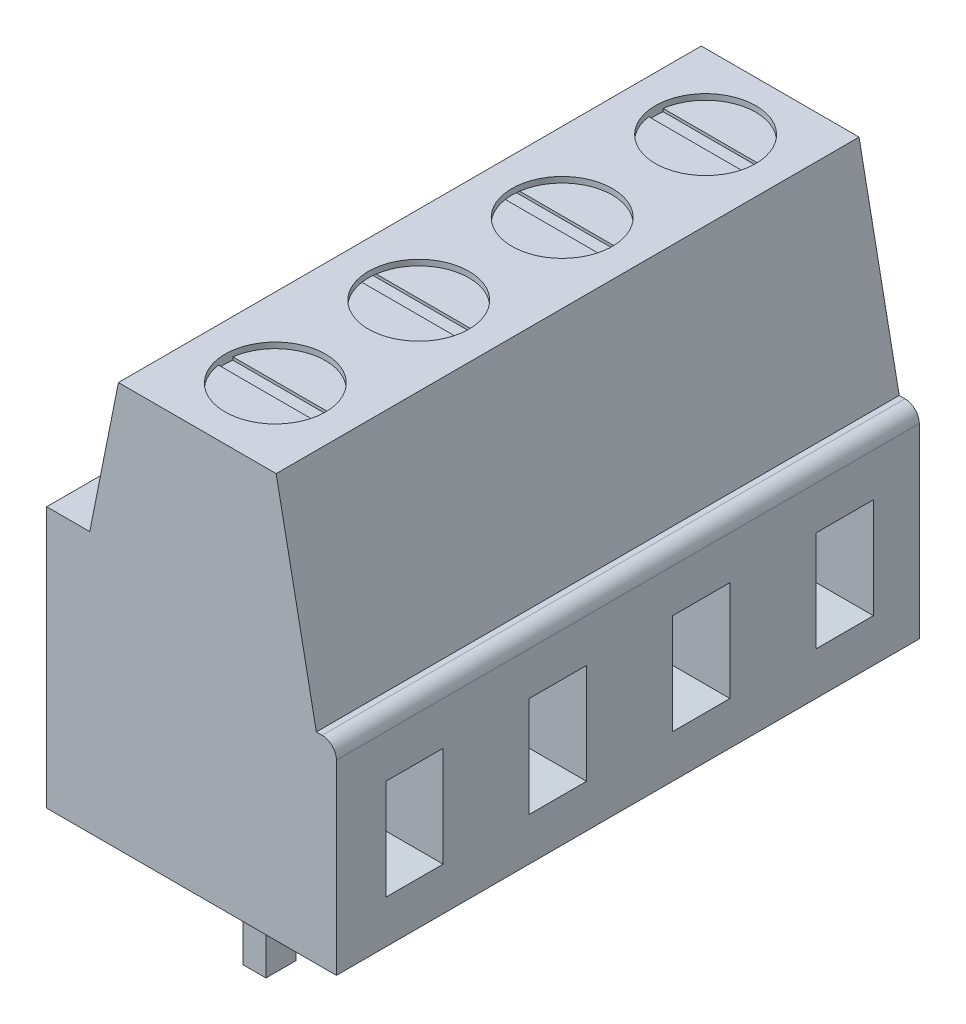
SolidWorks part; units mm, degrees
ref_plane "Front Plane" through (0, 0, 0) normal (0, 0, 1) x (1, 0, 0)
ref_plane "Top Plane" through (0, 0, 0) normal (0, 1, 0) x (1, 0, 0)
ref_plane "Right Plane" through (0, 0, 0) normal (1, 0, 0) x (0, 0, -1)
sketch "Sketch1" plane through (0, 0, 0) normal (0, 0, 1) x (1, 0, 0)
  line L0 (0, 1028.2) -> (0, 14.1) construction
  line L1 (0, 0) -> (25285.6582, 0) construction
  line L2 (0, 9.1) -> (1.5, 9.1)
  line L3 (0, 0) -> (10.1, 0)
  line L4 (0, 0) -> (0, 9.1)
  line L5 (2.5, 14.1) -> (8, 14.1)
  line L6 (10.1, 0) -> (10.1, 7)
  line L7 (1.5, 9.1) -> (2.5, 14.1)
  line L8 (8, 14.1) -> (9.4, 7)
  line L9 (9.4, 7) -> (10.1, 7)
  line L10 (8, 14.1) -> (10.1, 14.1) construction
  line L11 (10.1, 7) -> (10.1, 14.1) construction
  line L12 (0, 14.1) -> (2.5, 14.1) construction
  line L13 (0, 9.1) -> (0, 14.1) construction
  line L14 (0, 14.1) -> (0, 9.1) construction
  line L15 (0, 9.1) -> (0, -25285.6582) construction
  dimension "D1" = 14.1
  dimension "D2" = 10.1
  dimension "D3" = 1.5
  dimension "D4" = 5
  dimension "D5" = 2.5
  dimension "D6" = 5.5
  dimension "D7" = 7
  dimension "D8" = 0.7
extrude "Boss-Extrude1" add sketch "Sketch1" along normal mid plane 20.32
fillet "Fillet1" radius 0.5 1 edges at (10.1, 7, 0)
sketch "Sketch2" plane through (0, 14.1, 0) normal (0, 1, 0) x (1, 0, 0)
  line L0 (5.25, 10.16) -> (5.25, -10.16) construction
  line L1 (8, 10.16) -> (2.5, 10.16) construction
  line L2 (8, -10.16) -> (2.5, -10.16) construction
  line L3 (5.25, 7.56) -> (5.25, 2.56) construction
  circle A0 centre (5.25, 7.56) radius 1.75
  circle A1 centre (5.25, 2.56) radius 1.75
  circle A2 centre (5.25, -2.44) radius 1.75
  circle A3 centre (5.25, -7.44) radius 1.75
  dimension "D1" = 3.5
  dimension "D3" = 2.6
  dimension "D4" = 5
  dimension "D2" = 4
extrude "Cut-Extrude1" cut sketch "Sketch2" against normal blind 0.2 and the other way through all
sketch "Sketch3" plane through (0, 0, 0) normal (0, -1, 0) x (1, 0, 0)
  line L0 (5.05, 10.16) -> (5.05, -49989.84) construction
  line L1 (0, 10.16) -> (10.1, 10.16) construction
  line L2 (0, 0) -> (50000, 0) construction
  line L3 (5.25, 9.19) -> (5.25, 5.69) construction
  line L4 (4.65, 7.966) -> (5.45, 7.966)
  line L5 (4.65, 7.966) -> (4.65, 6.914)
  line L6 (4.65, 6.914) -> (5.45, 6.914)
  line L7 (5.45, 7.966) -> (5.45, 6.914)
  line L8 (4.65, 7.966) -> (5.45, 6.914) construction
  line L9 (4.65, 6.914) -> (5.45, 7.966) construction
  line L10 (7, 7.44) -> (3.5, 7.44) construction
  line L11 (5.45, 2.966) -> (5.45, 1.914)
  line L12 (4.65, 1.914) -> (5.45, 1.914)
  line L13 (4.65, 2.966) -> (4.65, 1.914)
  line L14 (4.65, 2.966) -> (5.45, 2.966)
  line L15 (5.45, -2.034) -> (5.45, -3.086)
  line L16 (4.65, -3.086) -> (5.45, -3.086)
  line L17 (4.65, -2.034) -> (4.65, -3.086)
  line L18 (4.65, -2.034) -> (5.45, -2.034)
  line L19 (5.45, -7.034) -> (5.45, -8.086)
  line L20 (4.65, -8.086) -> (5.45, -8.086)
  line L21 (4.65, -7.034) -> (4.65, -8.086)
  line L22 (4.65, -7.034) -> (5.45, -7.034)
  line L23 (5.45, 7.966) -> (5.45, 2.966) construction
  circle A0 centre (5.25, 7.44) radius 1.75 construction
  point P4 (5.05, 10.16)
  point P8 (5.05, 7.44)
  dimension "D1" = 1.052
  dimension "D2" = 0.8
  dimension "D3" = 4
  dimension "D4" = 5
extrude "Boss-Extrude2" add sketch "Sketch3" along normal blind 3.5
sketch "Sketch4" plane through (10.1, 0, 0) normal (1, 0, 0) x (0, 0, -1)
  line L0 (0, 0) -> (0, -50000) construction
  line L1 (-10.16, 3.25) -> (49989.84, 3.25) construction
  line L2 (-10.16, 0) -> (-10.16, 6.5) construction
  line L3 (-7.44, -3.5) -> (-7.44, 49996.5) construction
  line L4 (-6.914, -3.5) -> (-7.966, -3.5) construction
  line L5 (-3.44, 5) -> (-3.44, 1.5)
  line L6 (-8.44, 5) -> (-6.44, 5)
  line L7 (-8.44, 5) -> (-8.44, 1.5)
  line L8 (-8.44, 1.5) -> (-6.44, 1.5)
  line L9 (-6.44, 5) -> (-6.44, 1.5)
  line L10 (-8.44, 5) -> (-6.44, 1.5) construction
  line L11 (-8.44, 1.5) -> (-6.44, 5) construction
  line L12 (-3.44, 5) -> (-1.44, 5)
  line L13 (-1.44, 5) -> (-1.44, 1.5)
  line L14 (-3.44, 1.5) -> (-1.44, 1.5)
  line L15 (1.56, 5) -> (1.56, 1.5)
  line L16 (1.56, 5) -> (3.56, 5)
  line L17 (3.56, 5) -> (3.56, 1.5)
  line L18 (1.56, 1.5) -> (3.56, 1.5)
  line L19 (6.56, 5) -> (6.56, 1.5)
  line L20 (6.56, 5) -> (8.56, 5)
  line L21 (8.56, 5) -> (8.56, 1.5)
  line L22 (6.56, 1.5) -> (8.56, 1.5)
  line L23 (-8.44, 5) -> (-3.44, 5) construction
  point P7 (-10.16, 3.25)
  point P12 (-7.44, -3.5)
  point P13 (-7.44, 3.25)
  dimension "D1" = 3.5
  dimension "D2" = 2
  dimension "D4" = 5
  dimension "D3" = 4
extrude "Cut-Extrude2" cut sketch "Sketch4" against normal blind 2 draft 10
sketch "Sketch5" plane through (0, 13.9, 0) normal (0, 1, 0) x (1, 0, 0)
  line L0 (5.25, 7.56) -> (50005.25, 7.56) construction
  line L1 (3.3427, 2.81) -> (7.3435, 2.81)
  line L2 (3.3427, 7.81) -> (7.3435, 7.81)
  line L3 (3.3427, 7.81) -> (3.3427, 7.31)
  line L4 (3.3427, 7.31) -> (7.3435, 7.31)
  line L5 (7.3435, 7.81) -> (7.3435, 7.31)
  line L6 (3.3427, 2.81) -> (3.3427, 2.31)
  line L7 (3.3427, 2.31) -> (7.3435, 2.31)
  line L8 (7.3435, 2.81) -> (7.3435, 2.31)
  line L9 (3.3427, -2.19) -> (7.3435, -2.19)
  line L10 (3.3427, -2.19) -> (3.3427, -2.69)
  line L11 (3.3427, -2.69) -> (7.3435, -2.69)
  line L12 (7.3435, -2.19) -> (7.3435, -2.69)
  line L13 (3.3427, -7.19) -> (7.3435, -7.19)
  line L14 (3.3427, -7.19) -> (3.3427, -7.69)
  line L15 (3.3427, -7.69) -> (7.3435, -7.69)
  line L16 (7.3435, -7.19) -> (7.3435, -7.69)
  line L17 (3.3427, -12.19) -> (7.3435, -12.19)
  line L18 (3.3427, -12.19) -> (3.3427, -12.69)
  line L19 (3.3427, -12.69) -> (7.3435, -12.69)
  line L20 (7.3435, -12.19) -> (7.3435, -12.69)
  line L21 (3.3427, 7.81) -> (3.3427, 2.81) construction
  circle A0 centre (5.25, 7.56) radius 1.75 construction
  circle A1 centre (5.25, 7.56) radius 1.75
  circle A2 centre (5.25, 2.56) radius 1.75
  circle A3 centre (5.25, -2.44) radius 1.75
  circle A4 centre (5.25, -7.44) radius 1.75
  circle A5 centre (5.25, -12.44) radius 1.75
  circle M7 centre (5.25, -7.44) radius 1.75
  dimension "D1" = 0.5
  dimension "D2" = 0.25
  dimension "D4" = 5
  dimension "D3" = 5
extrude "Cut-Extrude3" cut sketch "Sketch5" against normal blind 0.1 contours L4 A1 L2 | L15 L13 M7 | L1 L8 L7 L6 | L9 L12 L11 L10
equation "\"D2@Sketch5\"=\"D1@Sketch5\"/2"
